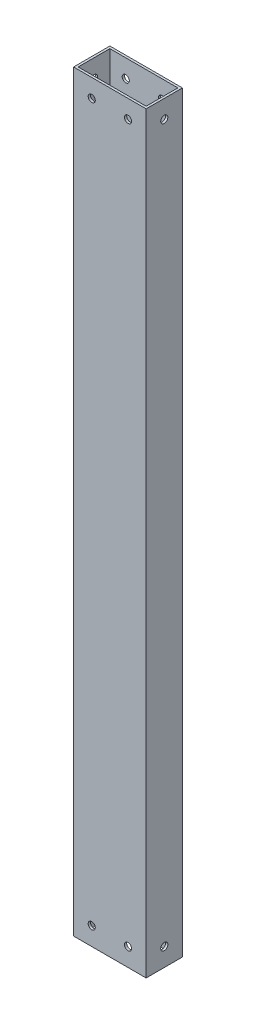
SolidWorks part; units mm, degrees
ref_plane "Front Plane" through (0, 0, 0) normal (0, 0, 1) x (1, 0, 0)
ref_plane "Top Plane" through (0, 0, 0) normal (0, 1, 0) x (1, 0, 0)
ref_plane "Right Plane" through (0, 0, 0) normal (1, 0, 0) x (0, 0, -1)
sketch "Sketch1" plane through (0, 0, 0) normal (0, 0, 1) x (1, 0, 0)
  line L1 (-25.4, -263.525) -> (25.4, -263.525)
  line L2 (-25.4, -263.525) -> (-25.4, 263.525)
  line L3 (-25.4, 263.525) -> (25.4, 263.525)
  line L4 (25.4, -263.525) -> (25.4, 263.525)
  line L5 (-25.4, -263.525) -> (25.4, 263.525) construction
  line L6 (-25.4, 263.525) -> (25.4, -263.525) construction
  point P0 (0, 0)
  dimension "D1" = 50.8
  dimension "D2" = 527.05
extrude "Boss-Extrude1" add sketch "Sketch1" along normal mid plane 25.4
shell "Shell1" thickness 1.5875
sketch "Sketch2" plane through (0, 0, 0) normal (0, 0, 1) x (1, 0, 0)
  line L0 (-25.4, 263.525) -> (-25.4, -263.525) construction
  line L1 (-25.4, -263.525) -> (25.4, -263.525) construction
  line L2 (-25.4, 0) -> (25.4, 0) construction
  line L3 (25.4, -263.525) -> (25.4, 263.525) construction
  circle A0 centre (-12.7, -250.825) radius 2.4892
  circle A1 centre (12.7, -250.825) radius 2.4892
  circle A2 centre (12.7, 250.825) radius 2.4892
  circle A3 centre (-12.7, 250.825) radius 2.4892
  dimension "D1" = 4.9784
  dimension "D3" = 25.4
  dimension "D2" = 12.7
  dimension "D4" = 12.7
extrude "Cut-Extrude1" cut sketch "Sketch2" against normal through all both and the other way through all
sketch "Sketch3" plane through (0, 0, 0) normal (1, 0, 0) x (0, 0, -1)
  line L0 (-12.7, -263.525) -> (12.7, -263.525) construction
  line L1 (-12.7, 263.525) -> (12.7, 263.525) construction
  circle A0 centre (0, -250.825) radius 2.4892
  circle A1 centre (0, 250.825) radius 2.4892
  point P6 (0, -263.525)
  point P9 (0, 263.525)
  point P10 (0, 0)
  dimension "D1" = 4.9784
  dimension "D2" = 12.7
  dimension "D3" = 12.7
extrude "Cut-Extrude2" cut sketch "Sketch3" against normal through all both and the other way through all
